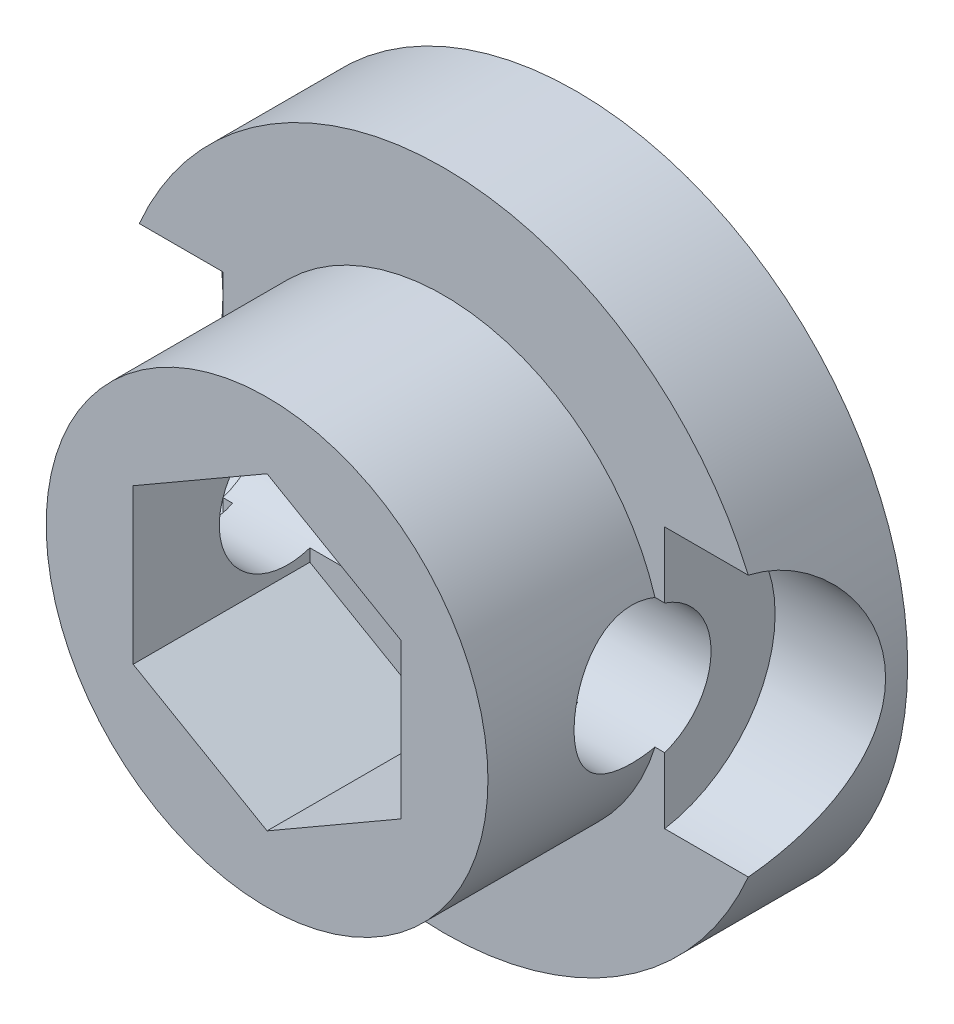
SolidWorks part; units mm, degrees
ref_plane "Front Plane" through (0, 0, 0) normal (0, 0, 1) x (1, 0, 0)
ref_plane "Top Plane" through (0, 0, 0) normal (0, 1, 0) x (1, 0, 0)
ref_plane "Right Plane" through (0, 0, 0) normal (1, 0, 0) x (0, 0, -1)
sketch "Sketch1" plane through (0, 0, 0) normal (0, 0, 1) x (1, 0, 0)
  line L2 (-3.0311, 1.75) -> (0, 3.5)
  line L3 (0, 3.5) -> (3.0311, 1.75)
  line L4 (3.0311, 1.75) -> (3.0311, -1.75)
  line L5 (3.0311, -1.75) -> (0, -3.5)
  line L6 (0, -3.5) -> (-3.0311, -1.75)
  line L7 (-3.0311, -1.75) -> (-3.0311, 1.75)
  circle A0 centre (0, 0) radius 5
  point P7 (0, 0)
  point P10 (0, 0)
extrude "Boss-Extrude2" add sketch "Sketch1" along normal blind 7
ref_plane "Plane1" through (0, 0, 0) normal (-1, 0, 0) x (0, 0, 1)
sketch "Sketch3" plane through (0, 0, 0) normal (0, 0, 1) x (1, 0, 0)
  circle A0 centre (0, 0) radius 7.5
extrude "Boss-Extrude3" add sketch "Sketch3" along normal blind 3
sketch "Sketch2" plane through (0, 0, 0) normal (-1, 0, 0) x (0, 0, 1)
  line L0 (0, 0) -> (7, 0) construction
  line L1 (7, -5) -> (7, 5) construction
  circle A0 centre (3.5, 0) radius 1.55
extrude "Cut-Extrude1" cut sketch "Sketch2" against normal blind 5 and the other way blind 5
ref_plane "Plane2" through (-5, 0, 0) normal (-1, 0, 0) x (0, 0, 1)
ref_plane "Plane3" through (5, 0, 0) normal (-1, 0, 0) x (0, 0, 1)
sketch "Sketch4" plane through (-5, 0, 0) normal (-1, 0, 0) x (0, 0, 1)
  circle A0 centre (3.5, 0) radius 3
extrude "Cut-Extrude2" cut sketch "Sketch4" along normal blind 2.5
sketch "Sketch5" plane through (5, 0, 0) normal (-1, 0, 0) x (0, 0, 1)
  circle A0 centre (3.5, 0) radius 3
extrude "Cut-Extrude3" cut sketch "Sketch5" against normal blind 2.5
